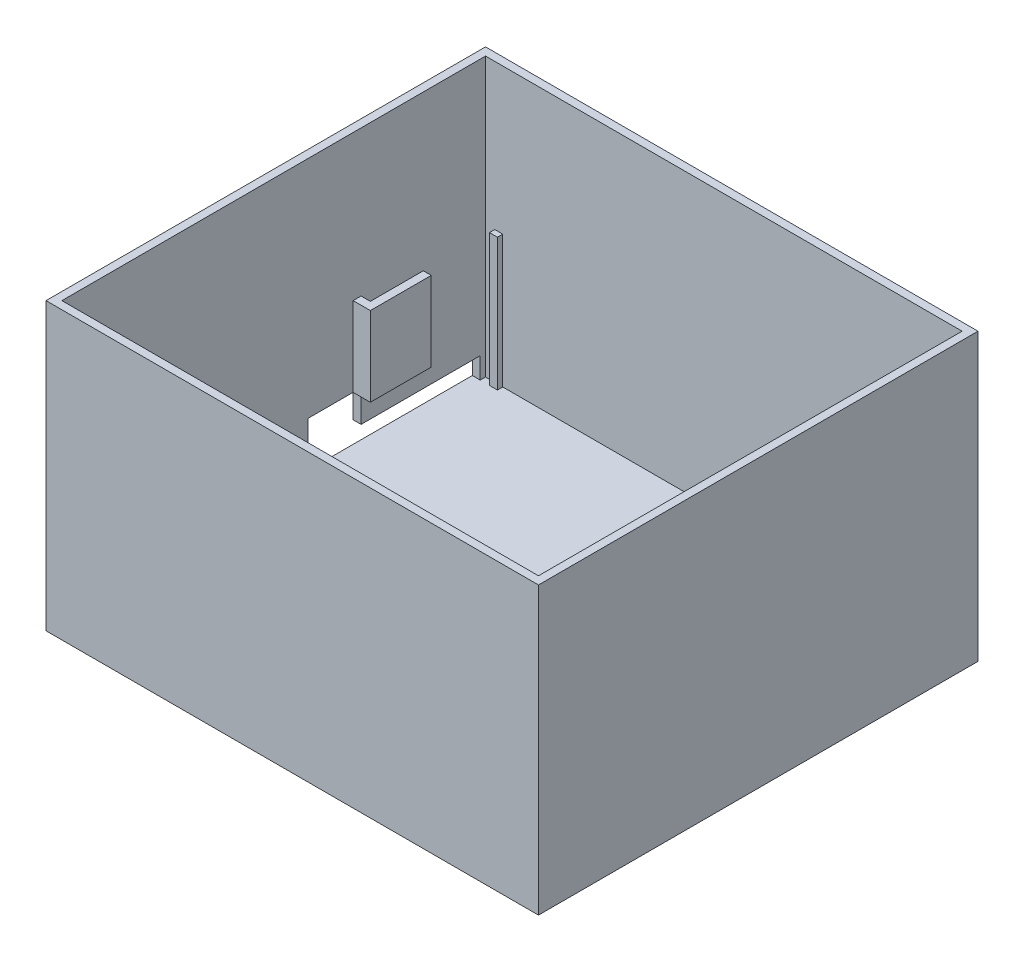
SolidWorks part; units mm, degrees
ref_plane "Front Plane" through (0, 0, 0) normal (0, 0, 1) x (1, 0, 0)
ref_plane "Top Plane" through (0, 0, 0) normal (0, 1, 0) x (1, 0, 0)
ref_plane "Right Plane" through (0, 0, 0) normal (1, 0, 0) x (0, 0, -1)
sketch "Sketch1" plane through (0, 0, 0) normal (0, 1, 0) x (1, 0, 0)
  line L1 (-89.25, 52.875) -> (96.75, 52.875)
  line L2 (-89.25, 52.875) -> (-89.25, -113.125)
  line L3 (-89.25, -113.125) -> (96.75, -113.125)
  line L4 (96.75, 52.875) -> (96.75, -113.125)
  dimension "D1" = 186
  dimension "D2" = 166
extrude "Boss-Extrude6" add sketch "Sketch1" along normal blind 3
sketch "Sketch7" plane through (0, 3, 0) normal (0, 1, 0) x (1, 0, 0)
  line L0 (96.75, -113.125) -> (96.75, 52.875) construction
  line L1 (-89.25, 52.875) -> (96.75, 52.875)
  line L2 (-89.25, 52.875) -> (-89.25, 49.875)
  line L3 (-89.25, 49.875) -> (96.75, 49.875)
  line L4 (96.75, 52.875) -> (96.75, 49.875)
  dimension "D1" = 3
sketch "Sketch8" plane through (0, 3, 0) normal (0, 1, 0) x (1, 0, 0)
  line L0 (-89.25, -113.125) -> (96.75, -113.125) construction
  line L1 (96.75, 49.875) -> (93.75, 49.875)
  line L2 (96.75, 49.875) -> (96.75, -113.125)
  line L3 (96.75, -113.125) -> (93.75, -113.125)
  line L4 (93.75, 49.875) -> (93.75, -113.125)
  dimension "D1" = 3
sketch "Sketch9" plane through (0, 3, 0) normal (0, 1, 0) x (1, 0, 0)
  line L0 (-89.25, 52.875) -> (-89.25, -113.125) construction
  line L1 (-89.25, -110.125) -> (93.75, -110.125)
  line L2 (-89.25, -110.125) -> (-89.25, -113.125)
  line L3 (-89.25, -113.125) -> (93.75, -113.125)
  line L4 (93.75, -110.125) -> (93.75, -113.125)
  dimension "D1" = 3
extrude "Boss-Extrude7" add sketch "Sketch9" along normal blind 105
extrude "Boss-Extrude8" add sketch "Sketch8" along normal blind 105
extrude "Boss-Extrude9" add sketch "Sketch7" along normal blind 105
sketch "Sketch11" plane through (0, 3, 0) normal (0, 1, 0) x (1, 0, 0)
  line L0 (93.75, -110.125) -> (-89.25, -110.125) construction
  line L1 (-89.25, 49.875) -> (-86.25, 49.875)
  line L2 (-89.25, 49.875) -> (-89.25, -110.125)
  line L3 (-89.25, -110.125) -> (-86.25, -110.125)
  line L4 (-86.25, 49.875) -> (-86.25, -110.125)
  dimension "D1" = 3
extrude "Boss-Extrude10" add sketch "Sketch11" along normal blind 105
sketch "Sketch12" plane through (0, 3, 0) normal (0, 1, 0) x (1, 0, 0)
  line L0 (-86.25, -110.125) -> (-86.25, 49.875) construction
  line L1 (-86.25, -51.125) -> (93.75, -51.125)
  line L2 (-86.25, -51.125) -> (-86.25, -54.125)
  line L3 (-86.25, -54.125) -> (93.75, -54.125)
  line L4 (93.75, -51.125) -> (93.75, -54.125)
  line L5 (93.75, 49.875) -> (93.75, -110.125) construction
  line L6 (-86.25, 49.875) -> (93.75, 49.875) construction
  dimension "D1" = 3
  dimension "D2" = 101
extrude "Boss-Extrude11" add sketch "Sketch12" along normal blind 20
sketch "Sketch13" plane through (-86.25, 0, 0) normal (1, 0, 0) x (0, 0, -1)
  line L0 (49.875, 108) -> (49.875, 3) construction
  line L1 (47.875, 3) -> (2.875, 3)
  line L2 (47.875, 3) -> (47.875, 11)
  line L3 (47.875, 11) -> (2.875, 11)
  line L4 (2.875, 3) -> (2.875, 11)
  line L5 (-51.125, 3) -> (49.875, 3) construction
  dimension "D1" = 8
  dimension "D2" = 45
  dimension "D3" = 2
  dimension "D4" = 0
extrude "Cut-Extrude5" cut sketch "Sketch13" against normal blind 3
sketch "Sketch18" plane through (-89.25, 0, 0) normal (-1, 0, 0) x (0, 0, 1)
  line L1 (-2.875, 3) -> (17.125, 3)
  line L2 (-2.875, 3) -> (-2.875, 23)
  line L3 (-2.875, 23) -> (17.125, 23)
  line L4 (17.125, 3) -> (17.125, 23)
  dimension "D1" = 20
  dimension "D2" = 20
sketch "Sketch20" plane through (0, 3, 0) normal (0, 1, 0) x (1, 0, 0)
  line L0 (-86.25, 49.875) -> (93.75, 49.875) construction
  line L1 (-82.75, 49.875) -> (-79.75, 49.875)
  line L2 (-82.75, 49.875) -> (-82.75, 47.875)
  line L3 (-82.75, 47.875) -> (-79.75, 47.875)
  line L4 (-79.75, 49.875) -> (-79.75, 47.875)
  line L5 (-86.25, 47.875) -> (-86.25, 49.875) construction
  dimension "D1" = 2
  dimension "D2" = 3
  dimension "D3" = 3.5
extrude "Boss-Extrude12" add sketch "Sketch20" along normal blind 50
extrude "Cut-Extrude6" cut sketch "Sketch18" against normal blind 3
sketch "Sketch22" plane through (-86.25, 0, 0) normal (1, 0, 0) x (0, 0, -1)
  line L1 (2.875, 23) -> (-0.125, 23)
  line L2 (2.875, 23) -> (2.875, 53)
  line L3 (2.875, 53) -> (-0.125, 53)
  line L4 (-0.125, 23) -> (-0.125, 53)
  dimension "D1" = 3
  dimension "D2" = 30
extrude "Boss-Extrude13" add sketch "Sketch22" along normal blind 6.5
sketch "Sketch23" plane through (0, 0, -2.875) normal (0, 0, -1) x (-1, 0, 0)
  line L0 (79.75, 23) -> (86.25, 23) construction
  line L1 (82.75, 23) -> (79.75, 23)
  line L2 (82.75, 23) -> (82.75, 53)
  line L3 (82.75, 53) -> (79.75, 53)
  line L4 (79.75, 23) -> (79.75, 53)
  dimension "D1" = 3
extrude "Boss-Extrude15" add sketch "Sketch23" along normal blind 20
